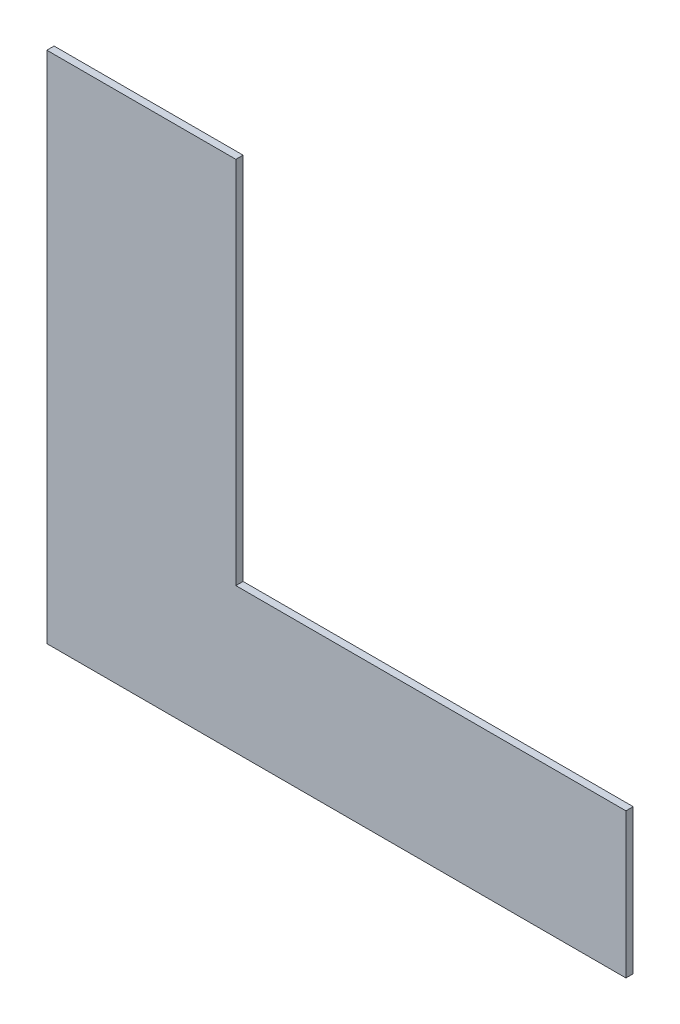
SolidWorks part; units mm, degrees
ref_plane "Plan de face" through (0, 0, 0) normal (0, 0, 1) x (1, 0, 0)
ref_plane "Plan de dessus" through (0, 0, 0) normal (0, 1, 0) x (1, 0, 0)
ref_plane "Plan de droite" through (0, 0, 0) normal (1, 0, 0) x (0, 0, -1)
sketch "Esquisse1" plane through (0, 0, 0) normal (0, 0, 1) x (1, 0, 0)
  line L0 (-198.956, 177.1265) -> (-198.956, -177.8735)
  line L1 (-198.956, -177.8735) -> (201.044, -177.8735)
  line L2 (201.044, -177.8735) -> (201.044, -77.8735)
  line L3 (-198.956, 177.1265) -> (-68.386, 177.1265)
  line L4 (201.044, -77.8735) -> (-68.386, -77.8735)
  line L5 (-68.386, -77.8735) -> (-68.386, 177.1265)
  dimension "D1" = 130.57
extrude "Boss.-Extru.1" add sketch "Esquisse1" along normal blind 5
